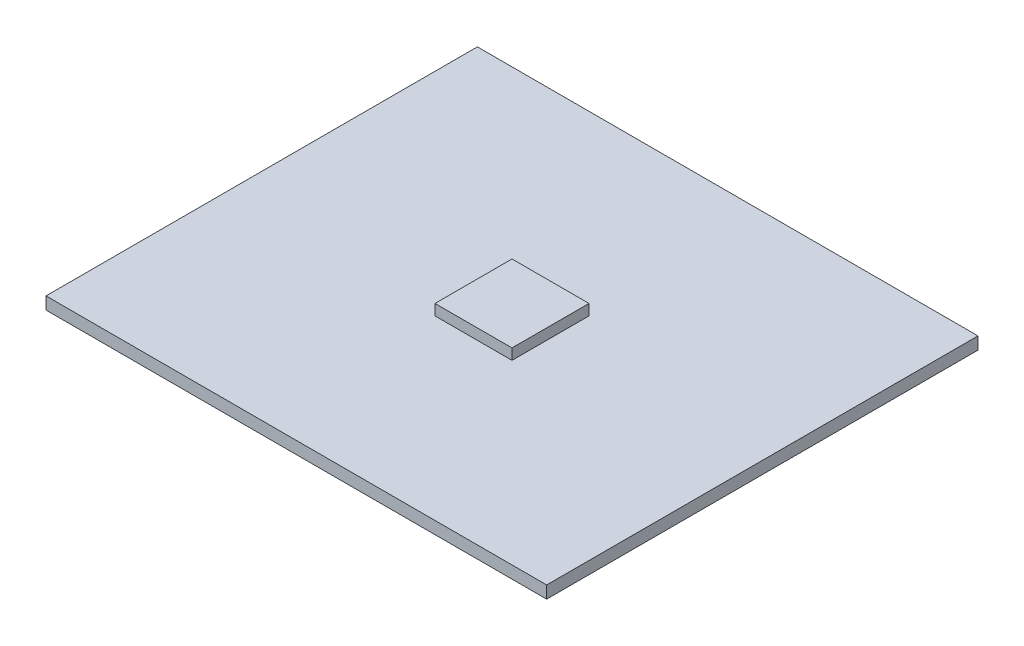
SolidWorks part; units mm, degrees
ref_plane "Front Plane" through (0, 0, 0) normal (0, 0, 1) x (1, 0, 0)
ref_plane "Top Plane" through (0, 0, 0) normal (0, 1, 0) x (1, 0, 0)
ref_plane "Right Plane" through (0, 0, 0) normal (1, 0, 0) x (0, 0, -1)
sketch "Sketch1" plane through (0, 0, 0) normal (0, 1, 0) x (1, 0, 0)
  line L0 (-32.5, -28) -> (32.5, -28)
  line L1 (32.5, -28) -> (32.5, 28)
  line L2 (32.5, 28) -> (-32.5, 28)
  line L3 (-32.5, 28) -> (-32.5, -28)
extrude "Boss-Extrude1" add sketch "Sketch1" along normal blind 1.6
sketch "Sketch2" plane through (0, 0, 0) normal (0, 1, 0) x (1, 0, 0)
  line L0 (-5, -5) -> (5, -5)
  line L1 (5, -5) -> (5, 5)
  line L2 (5, 5) -> (-5, 5)
  line L3 (-5, 5) -> (-5, -5)
extrude "Boss-Extrude2" add sketch "Sketch2" along normal blind 3
